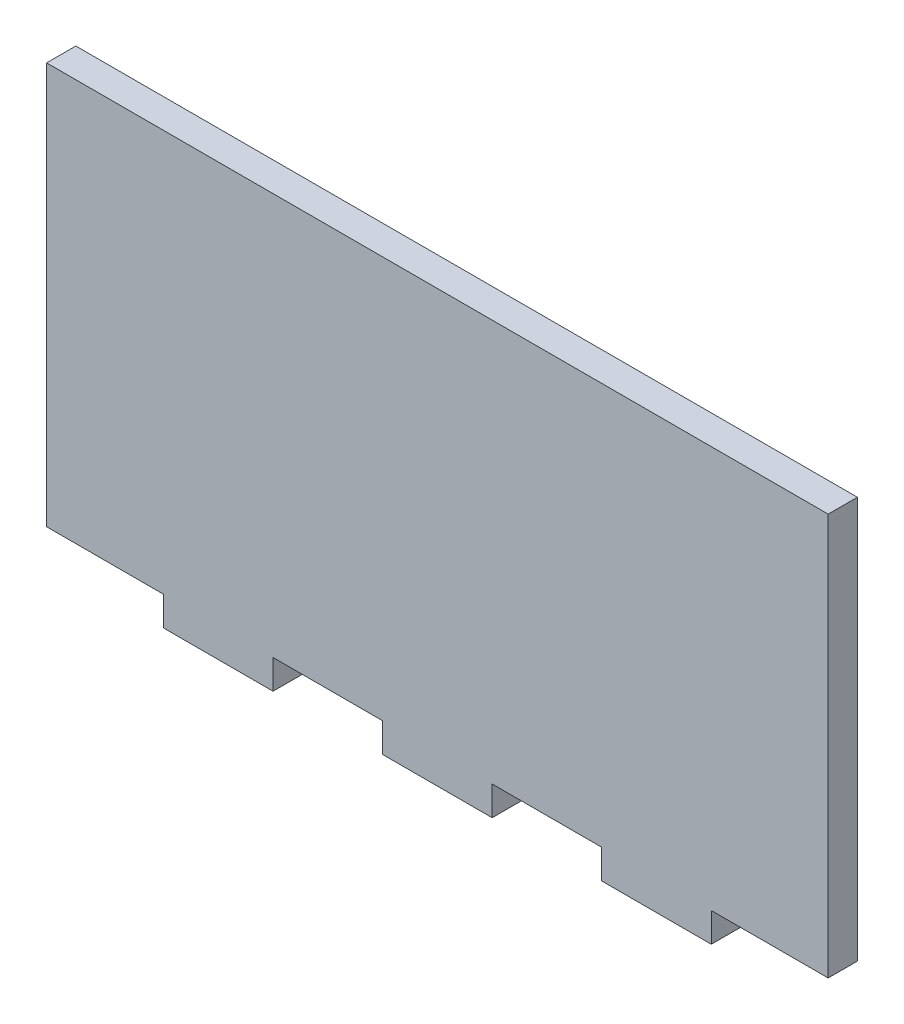
SolidWorks part; units mm, degrees
ref_plane "Front Plane" through (0, 0, 0) normal (0, 0, 1) x (1, 0, 0)
ref_plane "Top Plane" through (0, 0, 0) normal (0, 1, 0) x (1, 0, 0)
ref_plane "Right Plane" through (0, 0, 0) normal (1, 0, 0) x (0, 0, -1)
sketch "Sketch1" plane through (0, 0, 0) normal (0, 1, 0) x (1, 0, 0)
  line L1 (-53.5, -2) -> (53.5, -2)
  line L2 (-53.5, -2) -> (-53.5, 2)
  line L3 (-53.5, 2) -> (53.5, 2)
  line L4 (53.5, -2) -> (53.5, 2)
  line L5 (-53.5, -2) -> (53.5, 2) construction
  line L6 (-53.5, 2) -> (53.5, -2) construction
  point P0 (0, 0)
  dimension "D1" = 107
  dimension "D2" = 4
extrude "Boss-Extrude1" add sketch "Sketch1" along normal blind 55
sketch "Sketch2" plane through (0, 0, 0) normal (0, -1, 0) x (1, 0, 0)
  line L0 (-37.5, 2) -> (-37.5, -2)
  line L1 (-53.5, 2) -> (53.5, 2) construction
  line L2 (53.5, -2) -> (-53.5, -2) construction
  line L3 (-37.5, -2) -> (-22.5, -2)
  line L4 (-22.5, -2) -> (-22.5, 2)
  line L5 (-22.5, 2) -> (-37.5, 2)
  line L6 (-7.5, -2) -> (-7.5, 2)
  line L7 (-7.5, 2) -> (7.5, 2)
  line L8 (7.5, 2) -> (7.5, -2)
  line L9 (7.5, -2) -> (-7.5, -2)
  line L10 (22.5, -2) -> (22.5, 2)
  line L11 (22.5, 2) -> (37.5, 2)
  line L12 (37.5, 2) -> (37.5, -2)
  line L13 (37.5, -2) -> (22.5, -2)
  line L14 (-53.5, -2) -> (-53.5, 2) construction
  dimension "D1" = 15
  dimension "D2" = 16
  dimension "D3" = 15
  dimension "D4" = 15
  dimension "D5" = 15
  dimension "D6" = 15
extrude "Boss-Extrude2" add sketch "Sketch2" along normal blind 4
